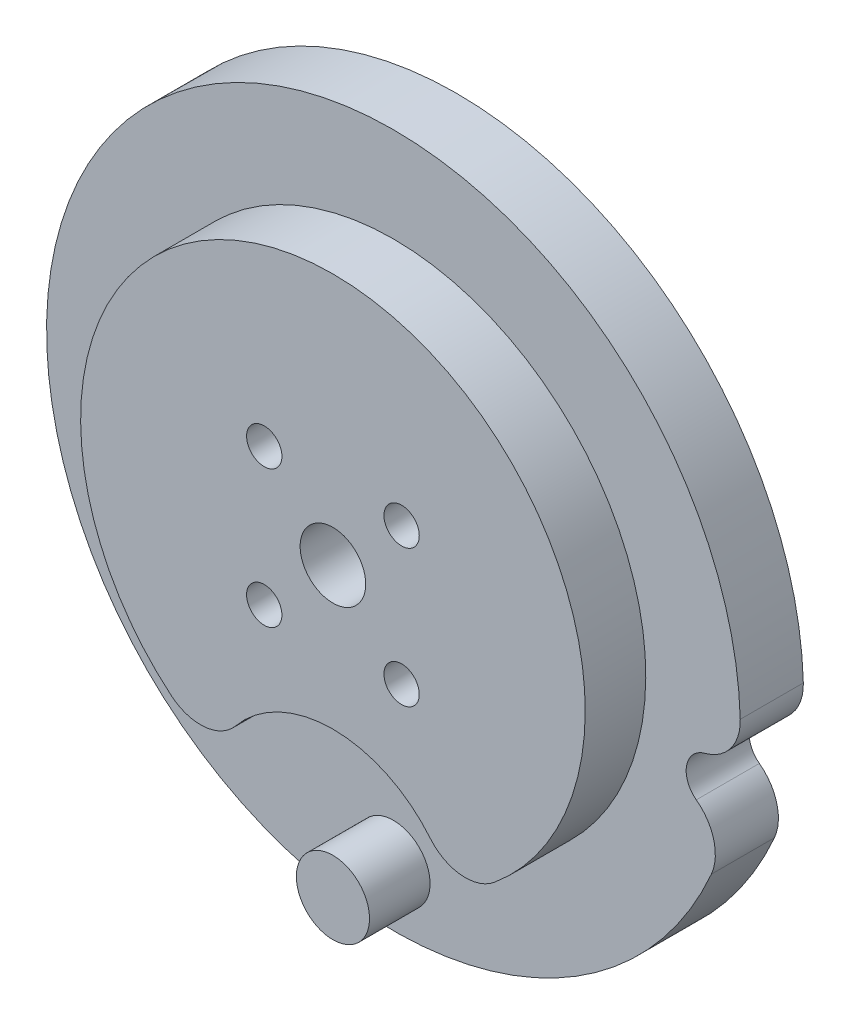
SolidWorks part; units mm, degrees
ref_plane "Front Plane" through (0, 0, 0) normal (0, 0, 1) x (1, 0, 0)
ref_plane "Top Plane" through (0, 0, 0) normal (0, 1, 0) x (1, 0, 0)
ref_plane "Right Plane" through (0, 0, 0) normal (1, 0, 0) x (0, 0, -1)
sketch "Sketch1" plane through (0, 0, 0) normal (0, 0, 1) x (1, 0, 0)
  line L1 (-6.9148, 6.9148) -> (6.9148, 6.9148) construction
  line L2 (-6.9148, 6.9148) -> (-6.9148, -6.9148) construction
  line L3 (-6.9148, -6.9148) -> (6.9148, -6.9148) construction
  line L4 (6.9148, 6.9148) -> (6.9148, -6.9148) construction
  line L5 (-6.9148, 6.9148) -> (6.9148, -6.9148) construction
  line L6 (-6.9148, -6.9148) -> (6.9148, 6.9148) construction
  circle A1 centre (0, 0) radius 34.925
  circle A8 centre (-6.9148, 6.9148) radius 1.778
  circle A9 centre (6.9148, 6.9148) radius 1.778
  circle A10 centre (6.9148, -6.9148) radius 1.778
  circle A11 centre (-6.9148, -6.9148) radius 1.778
  point P18 (0, 0)
  dimension "D1" = 19.558
  dimension "D2" = 3.556
  dimension "D4" = 69.85
extrude "Boss-Extrude1" add sketch "Sketch1" along normal blind 6.35
sketch "Sketch2" plane through (0, 0, 6.35) normal (0, 0, 1) x (1, 0, 0)
  arc A1 (11.865, -22.4585) -> (-11.865, -22.4585) centre (0, 0) ccw
  circle A2 centre (0, -26.9875) radius 12.7 construction
  arc A3 (-11.865, -22.4585) -> (11.865, -22.4585) centre (0, -26.9875) cw
  circle A4 centre (-6.9148, 6.9148) radius 1.778
  circle A5 centre (6.9148, 6.9148) radius 1.778
  circle A6 centre (0, -28.9719) radius 3.683
  point P6 (-11.865, -22.4585)
  point P7 (11.865, -22.4585)
  dimension "D1" = 7.366
  dimension "D3" = 50.8
  dimension "D4" = 25.4
  dimension "D2" = 26.9875
  dimension "D5" = 1.9844
extrude "Boss-Extrude2" add sketch "Sketch2" along normal blind 6.096
sketch "Sketch3" plane through (0, 0, 12.446) normal (0, 0, 1) x (1, 0, 0)
  circle A0 centre (0, 0) radius 3.302
  dimension "D1" = 6.604
extrude "Cut-Extrude1" cut sketch "Sketch3" against normal through all
fillet "Fillet1" radius 4.572 2 edges at (-11.865, -22.4585, 9.398) (11.865, -22.4585, 9.398)
sketch "Sketch4" plane through (0, 0, 0) normal (0, 0, -1) x (-1, 0, 0)
  circle A0 centre (-6.9148, -6.9148) radius 1.778
  circle A1 centre (6.9148, -6.9148) radius 1.778
extrude "Cut-Extrude2" cut sketch "Sketch4" against normal through all
sketch "Sketch5" plane through (0, 0, 0) normal (0, 0, -1) x (-1, 0, 0)
  line L0 (0, 0) -> (50000, 0) construction
  line L1 (0, 0) -> (0, -50000) construction
  circle A0 centre (-32.004, -6.223) radius 2.54
  dimension "D1" = 5.08
  dimension "D2" = 6.223
  dimension "D3" = 32.004
extrude "Cut-Extrude3" cut sketch "Sketch5" against normal through all
fillet "Fillet2" radius 4.7625 2 edges at (34.0634, -7.7098, 3.175) (34.4705, -5.6163, 3.175)
